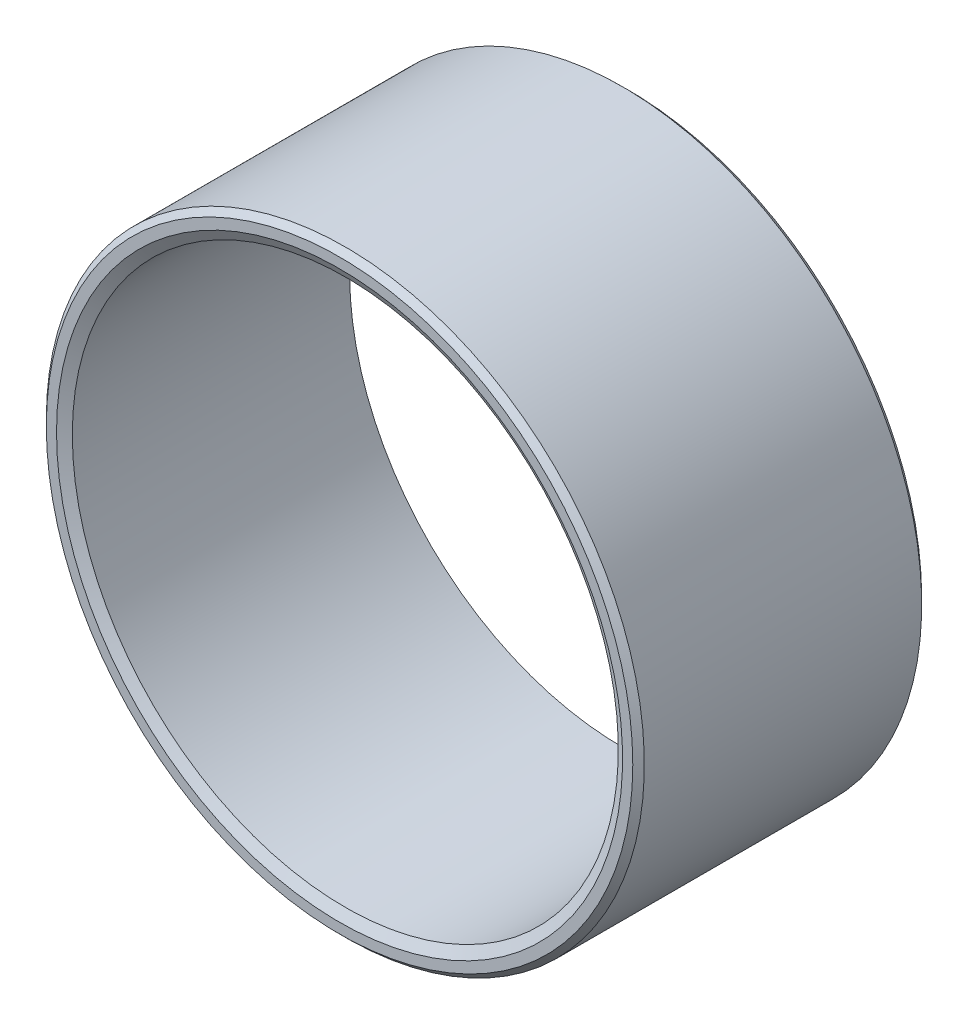
SolidWorks part; units mm, degrees
ref_plane "Front Plane" through (0, 0, 0) normal (0, 0, 1) x (1, 0, 0)
ref_plane "Top Plane" through (0, 0, 0) normal (0, 1, 0) x (1, 0, 0)
ref_plane "Right Plane" through (0, 0, 0) normal (1, 0, 0) x (0, 0, -1)
ref_plane "Plane1" through (0, 0, 0) normal (0, -1, 0) x (1, 0, 0)
sketch "Sketch1" plane through (0, 0, 0) normal (0, -1, 0) x (1, 0, 0)
  line L0 (12.8905, 0) -> (12.4414, 0)
  line L1 (12.4414, 0) -> (12.0015, -0.254)
  line L2 (12.0015, -0.254) -> (12.0015, -12.446)
  line L3 (12.0015, -12.446) -> (12.4414, -12.7)
  line L4 (12.4414, -12.7) -> (12.8905, -12.7)
  line L5 (12.8905, -12.7) -> (13.1445, -12.446)
  line L6 (13.1445, -12.446) -> (13.1445, -0.254)
  line L7 (13.1445, -0.254) -> (12.8905, 0)
  line L8 (0, 0) -> (0, -12.7) construction
revolve "Revolve1" add sketch "Sketch1" angle 360 about L8
